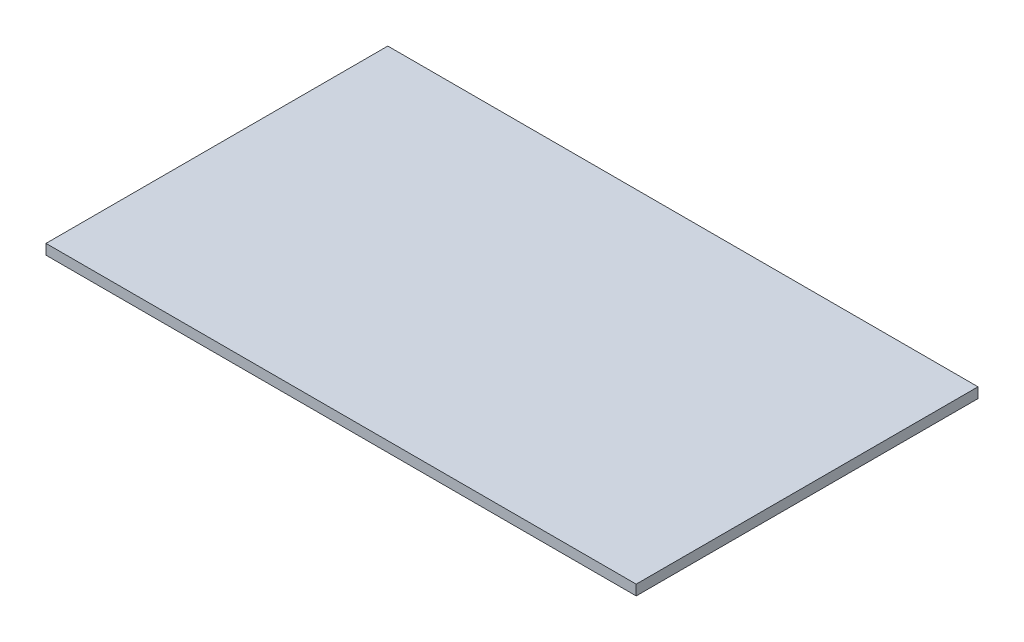
SolidWorks part; units mm, degrees
ref_plane "Front Plane" through (0, 0, 0) normal (0, 0, 1) x (1, 0, 0)
ref_plane "Top Plane" through (0, 0, 0) normal (0, 1, 0) x (1, 0, 0)
ref_plane "Right Plane" through (0, 0, 0) normal (1, 0, 0) x (0, 0, -1)
sketch "Esquisse1" plane through (0, 0, 0) normal (0, 1, 0) x (1, 0, 0)
  line L1 (-518, 300) -> (518, 300)
  line L2 (-518, 300) -> (-518, -300)
  line L3 (-518, -300) -> (518, -300)
  line L4 (518, 300) -> (518, -300)
  line L5 (-518, 300) -> (518, -300) construction
  line L6 (-518, -300) -> (518, 300) construction
  point P0 (0, 0)
extrude "Boss.-Extru.1" add sketch "Esquisse1" along normal blind 18
